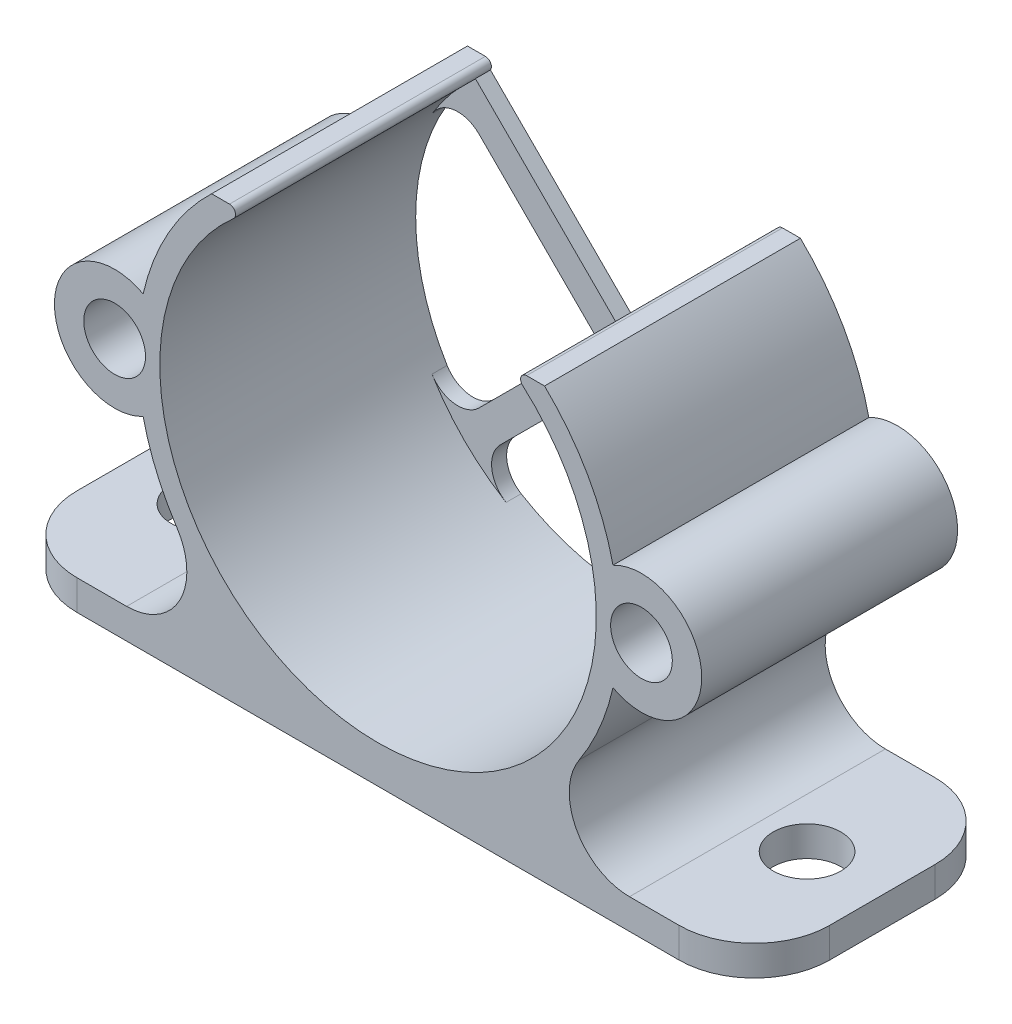
SolidWorks part; units mm, degrees
ref_plane "Plan de face" through (0, 0, 0) normal (0, 0, 1) x (1, 0, 0)
ref_plane "Plan de dessus" through (0, 0, 0) normal (0, 1, 0) x (1, 0, 0)
ref_plane "Plan de droite" through (0, 0, 0) normal (1, 0, 0) x (0, 0, -1)
sketch "Esquisse1" plane through (0, 0, 0) normal (0, 0, 1) x (1, 0, 0)
  line L0 (-8.75, 11.5623) -> (8.75, 11.5623)
  line L1 (-11.0595, 11.5623) -> (11.0595, 11.5623)
  line L2 (-17.5, 0) -> (17.5, 0)
  line L3 (-17.5, -4) -> (-22.5, -16)
  line L4 (-22.5, -16) -> (22.5, -16)
  line L5 (22.5, -16) -> (17.5, -4)
  circle A0 centre (0, 0) radius 14.5
  circle A1 centre (0, 0) radius 16
  circle A2 centre (-17.5, 0) radius 4
  circle A3 centre (17.5, 0) radius 4
  circle A4 centre (-17.5, 0) radius 2.05
  circle A5 centre (17.5, 0) radius 2.05
  dimension "D1" = 29
  dimension "D3" = 32
  dimension "D4" = 8
  dimension "D5" = 35
  dimension "D7" = 4.1
  dimension "D2" = 17.5
  dimension "D6" = 17.5
  dimension "D8" = 45
  dimension "D9" = 22.5
extrude "Boss.-Extru.2" add sketch "Esquisse1" along normal blind 17 contours A3 A0 A2 A1 | A4 A1 A2 | A4 L2 A0 A2 A1 | A4 A1 A2 A0 L2 | A2 A0 L1 A1 | A3 A1 L1 A0 | A5 L2 A0 A3 A1 | A5 A1 A3 A0 L2 | A5 A1 A3
sketch "Esquisse2" plane through (0, 0, 17) normal (0, 0, 1) x (1, 0, 0)
  line L1 (-25, -15) -> (25, -15)
  line L2 (-25, -15) -> (-25, -17)
  line L3 (-25, -17) -> (25, -17)
  line L4 (25, -15) -> (25, -17)
  arc A0 (-8.75, 11.5623) -> (8.75, 11.5623) centre (0, 0) ccw construction
  dimension "D1" = 15
  dimension "D2" = 2
  dimension "D3" = 25
  dimension "D4" = 25
extrude "Boss.-Extru.3" add sketch "Esquisse2" against normal blind 17
fillet "Congé2" radius 4 2 edges at (5.5678, -15, 8.5) (-5.5678, -15, 8.5)
sketch "Esquisse4" plane through (0, 0, 0) normal (0, 0, -1) x (-1, 0, 0)
  line L0 (0.4069, -0.4069) -> (0.7071, -0.7071)
  line L1 (25, -17) -> (-25, -17) construction
  line L2 (-17, -17) -> (-10.253, -10.253)
  line L3 (-14.8027, -13.3885) -> (-1.4142, 0)
  line L4 (-12.2449, -13.6591) -> (0, -1.4142)
  line L5 (21.5539, -20.1397) -> (1.4142, 0)
  line L6 (16.1226, -17.5368) -> (0, -1.4142)
  line L7 (0, 1.4142) -> (-10.151, 11.5652)
  line L8 (-1.4142, 0) -> (-12.9233, 11.5091)
  line L9 (10.253, 10.253) -> (11.3137, 11.3137)
  line L10 (0, 1.4142) -> (14.7142, 16.1284)
  line L11 (1.4142, 0) -> (20.2749, 18.8607)
  line L12 (10.253, -10.253) -> (17, -17)
  arc A0 (15.6071, 3.5238) -> (11.0595, 11.5623) centre (0, 0) ccw construction
  circle A2 centre (0, 0) radius 14.5
  arc A4 (-8.75, 11.5623) -> (8.75, 11.5623) centre (0, 0) ccw construction
  dimension "D3" = 1
  dimension "D1" = 90
  dimension "D2" = 45
  dimension "D4" = 1
  dimension "D5" = 1
  dimension "D6" = 1
extrude "Boss.-Extru.4" add sketch "Esquisse4" against normal blind 1
fillet "Congé3" radius 0.4 2 edges at (-8.75, 11.5623, 8.5) (8.75, 11.5623, 8.5)
fillet "Congé4" radius 2 6 edges at (-10.9357, 9.5215, 0.5) (10.9357, 9.5215, 0.5) (9.5215, -10.9357, 0.5) (10.9357, -9.5215, 0.5) (-10.9357, -9.5215, 0.5) (-9.5215, -10.9357, 0.5)
sketch "Esquisse5" plane through (0, -17, 0) normal (0, -1, 0) x (1, 0, 0)
  line L0 (-25, 8.5) -> (25, 8.5) construction
  line L1 (-25, 0) -> (-25, 17) construction
  line L2 (25, 0) -> (25, 17) construction
  circle A0 centre (-20, 8.5) radius 2.25
  circle A1 centre (20, 8.5) radius 2.25
  dimension "D1" = 4.5
  dimension "D2" = 4.5
  dimension "D3" = 5
  dimension "D4" = 5
extrude "Enlèv. mat.-Extru.1" cut sketch "Esquisse5" against normal up to surface (2 mm away) up to face at (-20.8516, -15, 8.5)
fillet "Congé5" radius 5 4 edges at (25, -16, 17) (25, -16, 0) (-25, -16, 0) (-25, -16, 17)
